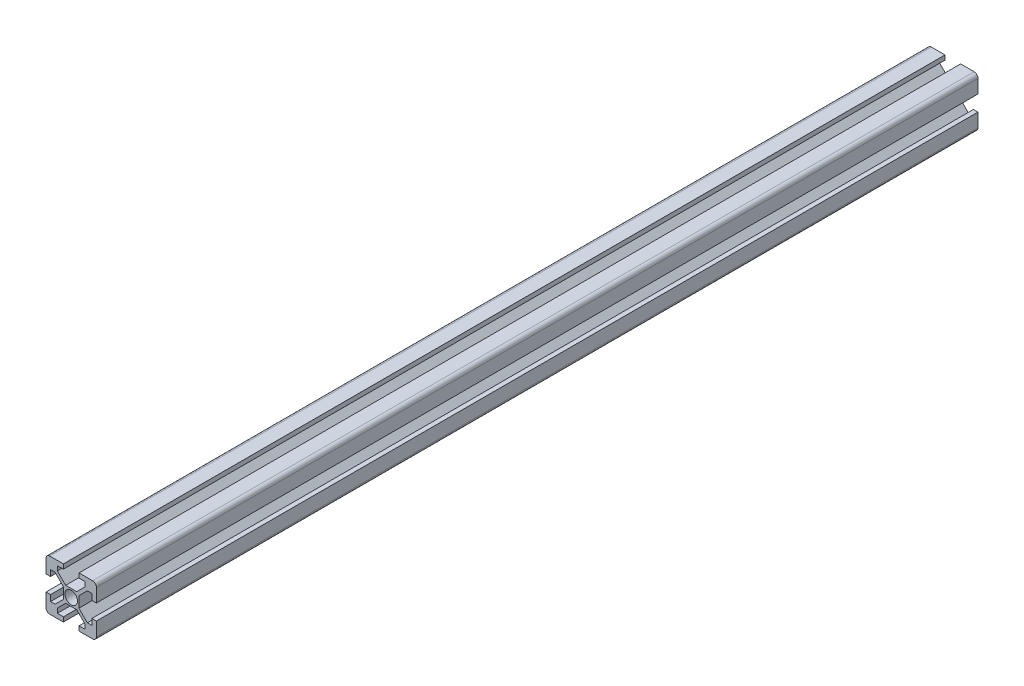
SolidWorks part; units mm, degrees
ref_plane "前视基准面" through (0, 0, 0) normal (0, 0, 1) x (1, 0, 0)
ref_plane "上视基准面" through (0, 0, 0) normal (0, 1, 0) x (1, 0, 0)
ref_plane "右视基准面" through (0, 0, 0) normal (1, 0, 0) x (0, 0, -1)
sketch "草图1" plane through (0, 0, 0) normal (0, 0, 1) x (1, 0, 0)
  line L0 (-10, -3.1) -> (-8.2, -3.1)
  line L1 (-8.5, 10) -> (8.5, 10)
  line L2 (-10, 8.5) -> (-10, -8.5)
  line L3 (-8.5, -10) -> (8.5, -10)
  line L4 (10, 8.5) -> (10, -8.5)
  line L5 (-10, 10) -> (10, -10) construction
  line L6 (-10, -10) -> (10, 10) construction
  line L7 (-3.0541, 3.1) -> (3.0541, 3.1)
  line L8 (-3.0541, 3.1) -> (-3.0541, -3.1)
  line L9 (-3.0541, -3.1) -> (3.0541, -3.1)
  line L10 (3.0541, 3.1) -> (3.0541, -3.1)
  line L11 (-3.0541, 3.1) -> (3.0541, -3.1) construction
  line L12 (-3.0541, -3.1) -> (3.0541, 3.1) construction
  line L13 (-8.2, -3.1) -> (-8.2, -5.5)
  line L14 (-8.2, -5.5) -> (-6.3971, -5.5)
  line L15 (-6.3971, -5.5) -> (-3.0541, -2.1571)
  line L16 (-5.5, 6.3971) -> (-2.1571, 3.0541)
  line L17 (-5.5, 8.2) -> (-5.5, 6.3971)
  line L18 (-3.1, 8.2) -> (-5.5, 8.2)
  line L19 (-3.1, 10) -> (-3.1, 8.2)
  line L20 (6.3971, 5.5) -> (3.0541, 2.1571)
  line L21 (8.2, 5.5) -> (6.3971, 5.5)
  line L22 (8.2, 3.1) -> (8.2, 5.5)
  line L23 (10, 3.1) -> (8.2, 3.1)
  line L24 (5.5, -6.3971) -> (2.1571, -3.0541)
  line L25 (5.5, -8.2) -> (5.5, -6.3971)
  line L26 (3.1, -8.2) -> (5.5, -8.2)
  line L27 (3.1, -10) -> (3.1, -8.2)
  line L28 (-3.1, -10) -> (-3.1, -8.2)
  line L29 (-3.1, -8.2) -> (-5.5, -8.2)
  line L30 (-5.5, -8.2) -> (-5.5, -6.3971)
  line L31 (-5.5, -6.3971) -> (-2.1571, -3.0541)
  line L32 (-8.2, 5.5) -> (-6.3971, 5.5)
  line L33 (-6.3971, 5.5) -> (-3.0541, 2.1571)
  line L34 (-8.2, 3.1) -> (-8.2, 5.5)
  line L35 (-10, 3.1) -> (-8.2, 3.1)
  line L36 (5.5, 8.2) -> (5.5, 6.3971)
  line L37 (5.5, 6.3971) -> (2.1571, 3.0541)
  line L38 (3.1, 8.2) -> (5.5, 8.2)
  line L39 (3.1, 10) -> (3.1, 8.2)
  line L40 (8.2, -5.5) -> (6.3971, -5.5)
  line L41 (6.3971, -5.5) -> (3.0541, -2.1571)
  line L42 (8.2, -3.1) -> (8.2, -5.5)
  line L43 (10, -3.1) -> (8.2, -3.1)
  circle A0 centre (0, 0) radius 2.5
  arc A1 (-10, 8.5) -> (-8.5, 10) centre (-8.5, 8.5) cw
  arc A2 (-10, -8.5) -> (-8.5, -10) centre (-8.5, -8.5) ccw
  arc A3 (8.5, 10) -> (10, 8.5) centre (8.5, 8.5) cw
  arc A4 (10, -8.5) -> (8.5, -10) centre (8.5, -8.5) cw
  point P0 (0, 0)
  point P20 (0, 0)
  point P26 (0, 0)
  point P32 (0, 0)
  point P38 (0, 0)
  point P60 (0, 0)
  dimension "D1" = 4
  dimension "D3" = 1.5
  dimension "D4" = 1.5
  dimension "D5" = 1.5
  dimension "D2" = 4
extrude "凸台-拉伸1" add sketch "草图1" along normal blind 350
